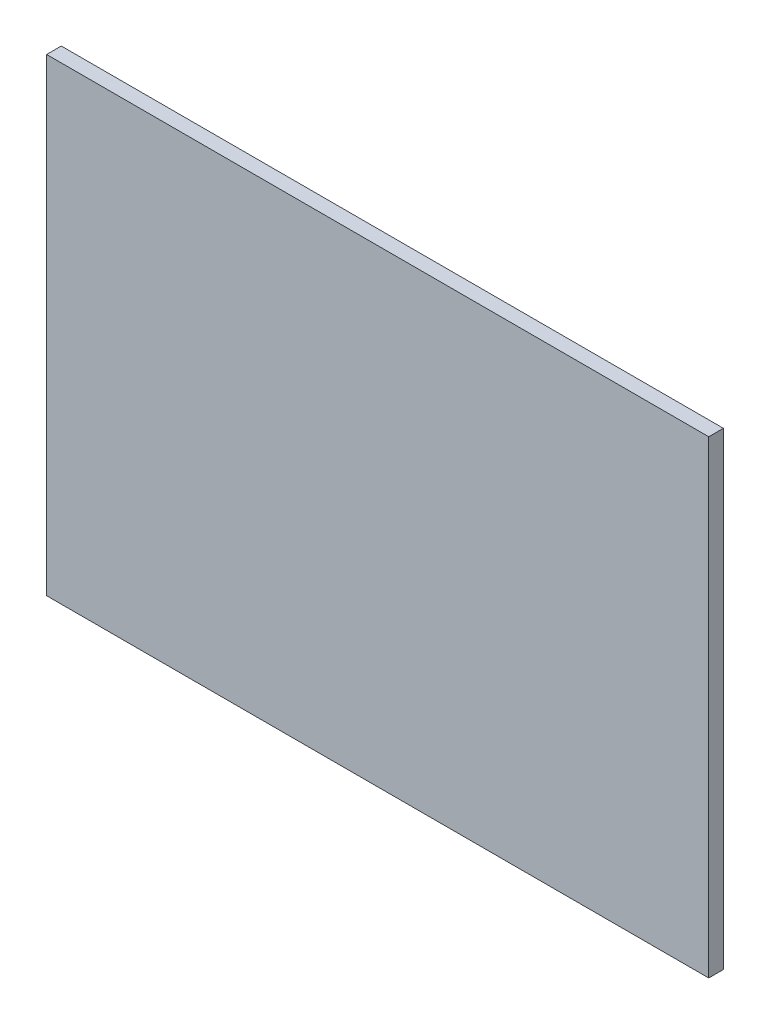
SolidWorks part; units mm, degrees
ref_plane "Front" through (0, 0, 0) normal (0, 0, 1) x (1, 0, 0)
ref_plane "Top" through (0, 0, 0) normal (0, 1, 0) x (1, 0, 0)
ref_plane "Right" through (0, 0, 0) normal (1, 0, 0) x (0, 0, -1)
sketch "Sketch1" plane through (0, 0, 0) normal (0, 0, 1) x (1, 0, 0)
  line L1 (-143.51, -101.6) -> (143.51, -101.6)
  line L2 (-143.51, -101.6) -> (-143.51, 101.6)
  line L3 (-143.51, 101.6) -> (143.51, 101.6)
  line L4 (143.51, -101.6) -> (143.51, 101.6)
  line L5 (-143.51, -101.6) -> (143.51, 101.6) construction
  line L6 (-143.51, 101.6) -> (143.51, -101.6) construction
  point P0 (0, 0)
  dimension "D1" = 287.02
  dimension "D2" = 203.2
extrude "Boss-Extrude1" add sketch "Sketch1" along normal mid plane 6.35 contours L3 L4 L1 L2
sketch "Sketch2" plane through (0, 0, 3.175) normal (0, 0, 1) x (1, 0, 0)
  line L0 (-143.51, 50.3205) -> (143.51, 50.3205) construction
  line L1 (-143.51, -101.6) -> (-143.51, 101.6) construction
  line L2 (143.51, -101.6) -> (143.51, 101.6) construction
  point P0 (-85.09, 85.8568)
  point P1 (74.93, 82.6015)
  point P2 (-138.176, 50.3205)
  point P3 (-57.15, 50.3205)
  point P4 (41.91, 50.3205)
  point P5 (-8.89, 50.3205)
  point P6 (92.71, 50.3205)
  point P7 (133.35, 50.3205)
  point P14 (0, 0)
  point P15 (0, 0)
  point P16 (0, 0)
  point P17 (0, 0)
  point P18 (0, 0)
  point P19 (0, 0)
  dimension "D1" = 58.42
  dimension "D2" = 68.58
  dimension "D3" = 5.334
  dimension "D4" = 86.36
  dimension "D5" = 134.62
  dimension "D6" = 10.16
  dimension "D7" = 50.8
  dimension "D8" = 101.6
